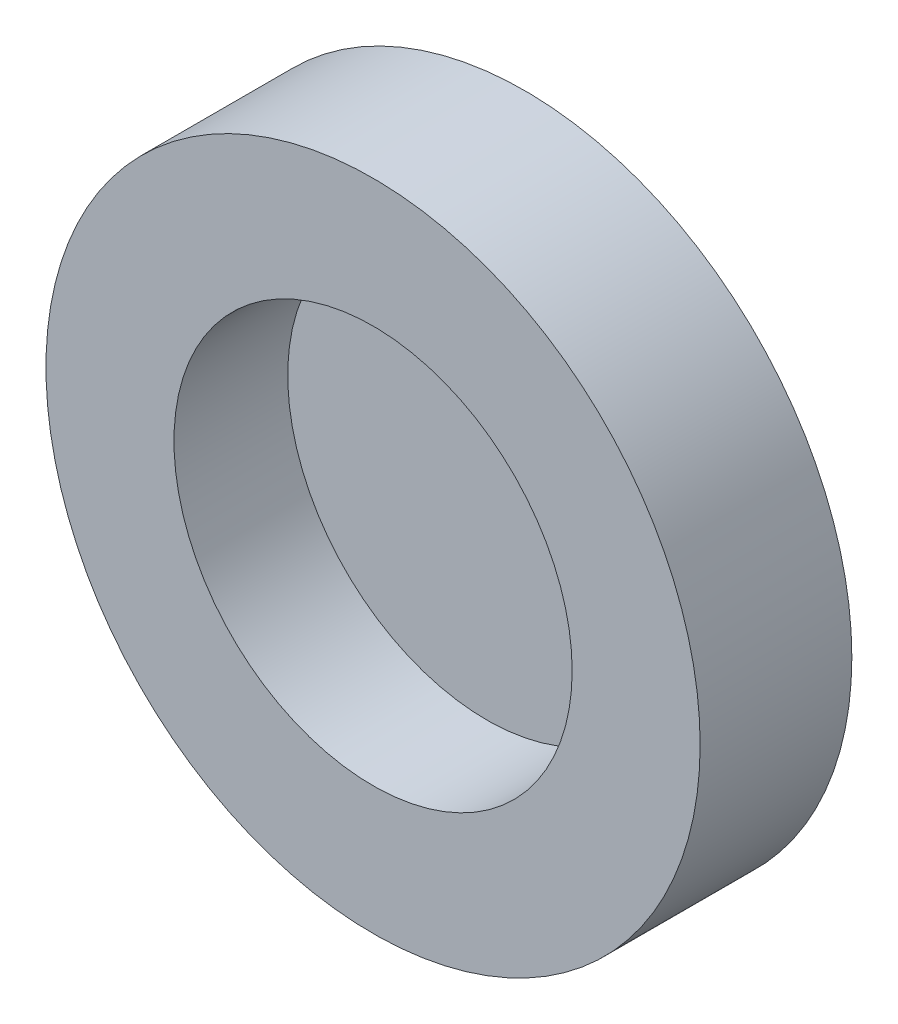
SolidWorks part; units mm, degrees
material "mach_pin"
ref_plane "Front Plane" through (0, 0, 0) normal (0, 0, 1) x (1, 0, 0)
ref_plane "Top Plane" through (0, 0, 0) normal (0, 1, 0) x (1, 0, 0)
ref_plane "Right Plane" through (0, 0, 0) normal (1, 0, 0) x (0, 0, -1)
sketch "Sketch1" plane through (0, 0, 0) normal (0, 0, 1) x (1, 0, 0)
  circle A0 centre (0, 0) radius 17.25
  dimension "D1" = 34.5
extrude "Boss-Extrude1" add sketch "Sketch1" along normal blind 8
sketch "Sketch2" plane through (0, 0, 8) normal (0, 0, 1) x (1, 0, 0)
  circle A0 centre (0, 0) radius 10.5
  dimension "D1" = 21
extrude "Cut-Extrude1" cut sketch "Sketch2" against normal blind 6 and the other way blind 1
